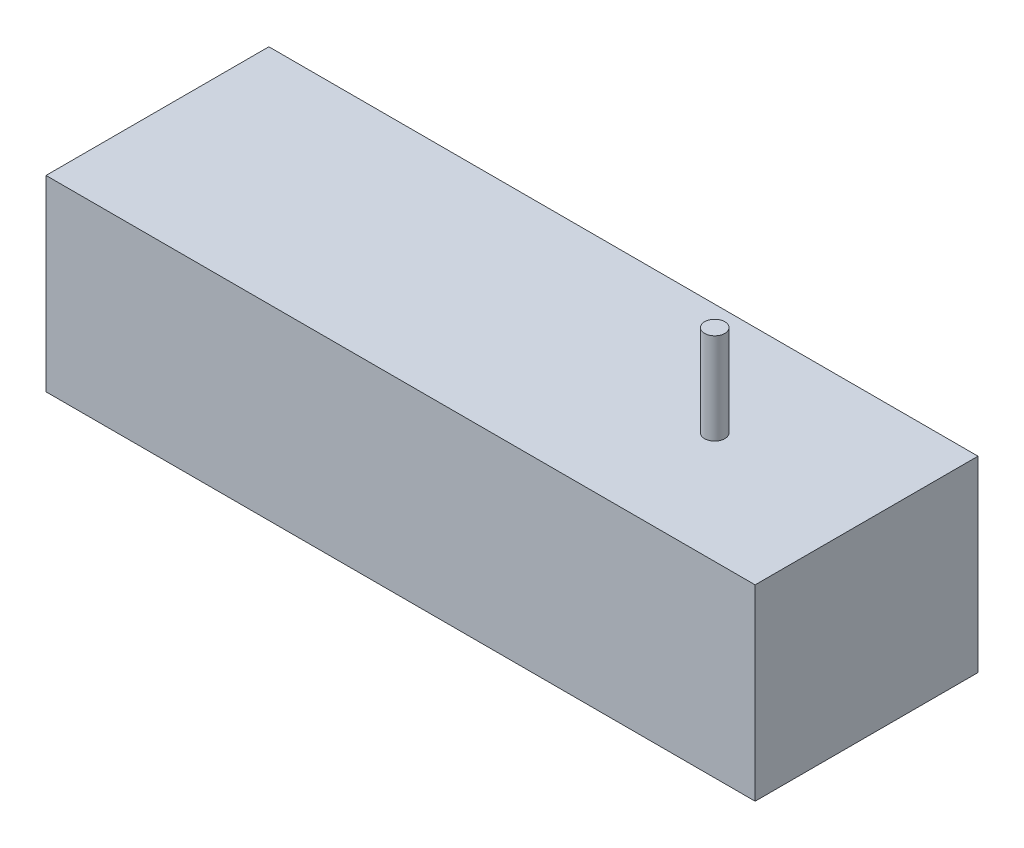
SolidWorks part; units mm, degrees
ref_plane "前基準面" through (0, 0, 0) normal (0, 0, 1) x (1, 0, 0)
ref_plane "上基準面" through (0, 0, 0) normal (0, 1, 0) x (1, 0, 0)
ref_plane "右基準面" through (0, 0, 0) normal (1, 0, 0) x (0, 0, -1)
sketch "草圖2" plane through (0, 0, 0) normal (0, 1, 0) x (1, 0, 0)
  line L1 (-35, 11) -> (35, 11)
  line L2 (-35, 11) -> (-35, -11)
  line L3 (-35, -11) -> (35, -11)
  line L4 (35, 11) -> (35, -11)
  line L5 (-35, 11) -> (35, -11) construction
  line L6 (-35, -11) -> (35, 11) construction
  point P0 (0, 0)
  dimension "D1" = 70
  dimension "D2" = 22
extrude "填料-伸長1" add sketch "草圖2" along normal blind 18.5
sketch "草圖3" plane through (0, 18.5, 0) normal (0, 1, 0) x (1, 0, 0)
  line L0 (-46.1438, 0) -> (44.8881, 0) construction
  line L1 (0, 15.9306) -> (0, -15.5382) construction
  circle A0 centre (20.0113, 0) radius 1
  dimension "D1" = 2
  dimension "D2" = 20.0113
extrude "填料-伸長2" add sketch "草圖3" along normal blind 9
